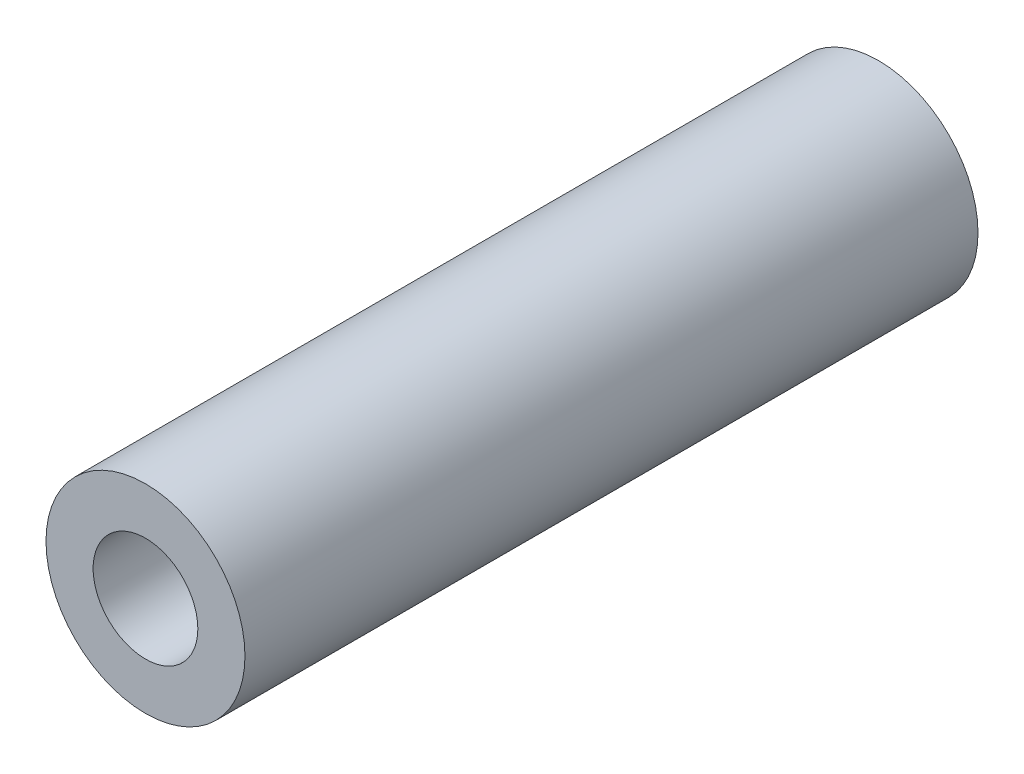
SolidWorks part; units mm, degrees
ref_plane "Front Plane" through (0, 0, 0) normal (0, 0, 1) x (1, 0, 0)
ref_plane "Top Plane" through (0, 0, 0) normal (0, 1, 0) x (1, 0, 0)
ref_plane "Right Plane" through (0, 0, 0) normal (1, 0, 0) x (0, 0, -1)
sketch "Sketch1" plane through (0, 0, 0) normal (0, 0, 1) x (1, 0, 0)
  circle A0 centre (0, 0) radius 2.5
  circle A1 centre (0, 0) radius 4.75
  dimension "D1" = 5
  dimension "D2" = 9.5
extrude "Boss-Extrude1" add sketch "Sketch1" along normal mid plane 35
